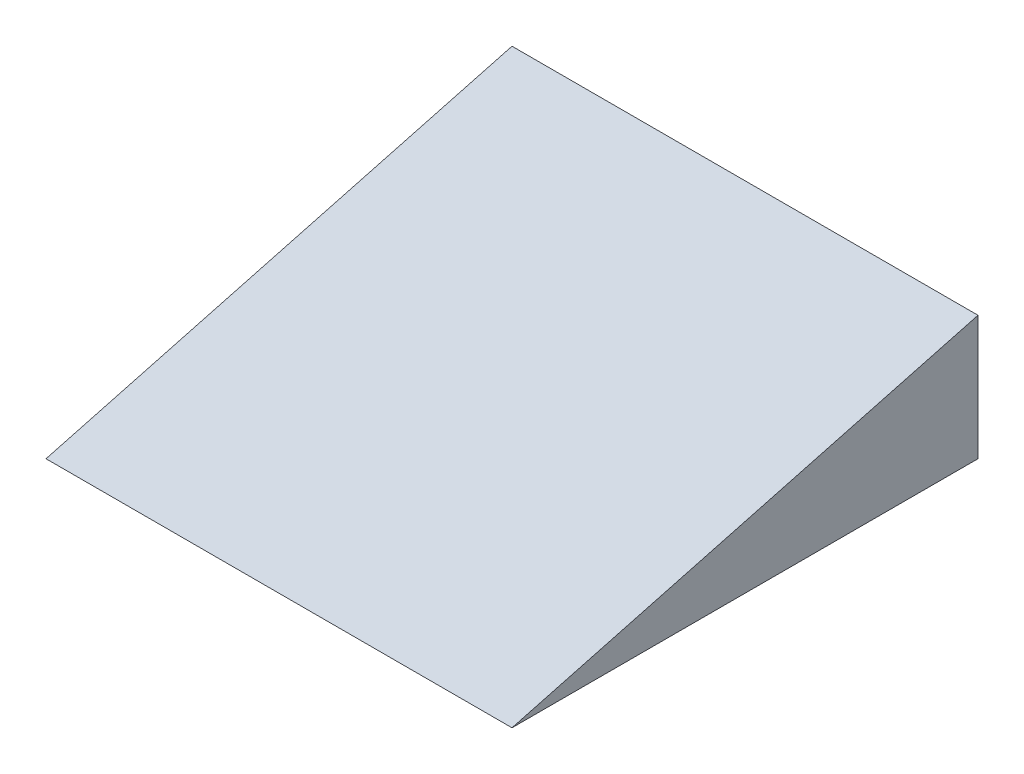
SolidWorks part; units mm, degrees
ref_plane "前视基准面" through (0, 0, 0) normal (0, 0, 1) x (1, 0, 0)
ref_plane "上视基准面" through (0, 0, 0) normal (0, 1, 0) x (1, 0, 0)
ref_plane "右视基准面" through (0, 0, 0) normal (1, 0, 0) x (0, 0, -1)
other "Configuration Table"
sketch "草图1" plane through (0, 0, 0) normal (1, 0, 0) x (0, 0, -1)
  line L0 (0, 0) -> (1500, 0)
  line L1 (1500, 0) -> (1500, 400)
  line L2 (1500, 400) -> (0, 0)
  dimension "D1" = 400
  dimension "D2" = 1500
extrude "凸台-拉伸1" add sketch "草图1" along normal blind 1500
